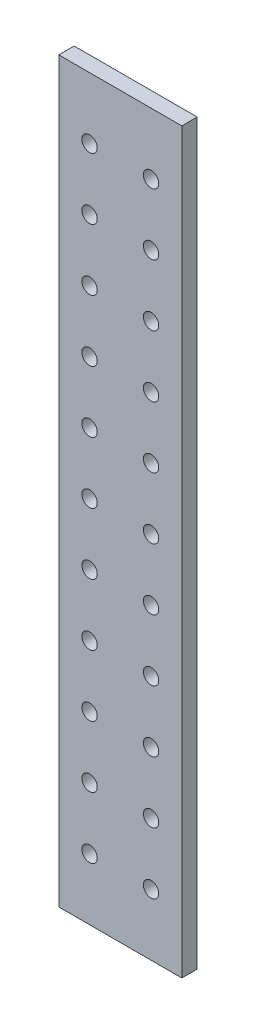
SolidWorks part; units mm, degrees
ref_plane "Front Plane" through (0, 0, 0) normal (0, 0, 1) x (1, 0, 0)
ref_plane "Top Plane" through (0, 0, 0) normal (0, 1, 0) x (1, 0, 0)
ref_plane "Right Plane" through (0, 0, 0) normal (1, 0, 0) x (0, 0, -1)
sketch "Sketch1" plane through (0, 0, 0) normal (0, 0, 1) x (1, 0, 0)
  line L1 (-25.4, 152.4) -> (25.4, 152.4)
  line L2 (-25.4, 152.4) -> (-25.4, -152.4)
  line L3 (-25.4, -152.4) -> (25.4, -152.4)
  line L4 (25.4, 152.4) -> (25.4, -152.4)
  line L5 (-25.4, 152.4) -> (25.4, -152.4) construction
  line L6 (-25.4, -152.4) -> (25.4, 152.4) construction
  point P0 (0, 0)
  dimension "D1" = 50.8
  dimension "D2" = 304.8
extrude "Boss-Extrude1" add sketch "Sketch1" along normal mid plane 6.35
sketch "Sketch2" plane through (0, 0, 0) normal (0, 0, 1) x (1, 0, 0)
  line L0 (25.4, 152.4) -> (-25.4, 152.4) construction
  line L1 (-25.4, 152.4) -> (-25.4, -152.4) construction
  circle A0 centre (-12.7, 127) radius 3.175
  circle A1 centre (12.7, 127) radius 3.175
  circle A2 centre (12.7, 101.6) radius 3.175
  circle A3 centre (12.7, 76.2) radius 3.175
  circle A4 centre (12.7, 50.8) radius 3.175
  circle A5 centre (12.7, 25.4) radius 3.175
  circle A6 centre (12.7, 0) radius 3.175
  circle A7 centre (12.7, -25.4) radius 3.175
  circle A8 centre (12.7, -50.8) radius 3.175
  circle A9 centre (12.7, -76.2) radius 3.175
  circle A10 centre (12.7, -101.6) radius 3.175
  circle A11 centre (-12.7, 101.6) radius 3.175
  circle A12 centre (-12.7, 76.2) radius 3.175
  circle A13 centre (-12.7, 50.8) radius 3.175
  circle A14 centre (-12.7, 25.4) radius 3.175
  circle A15 centre (-12.7, 0) radius 3.175
  circle A16 centre (-12.7, -25.4) radius 3.175
  circle A17 centre (-12.7, -50.8) radius 3.175
  circle A18 centre (-12.7, -76.2) radius 3.175
  circle A19 centre (-12.7, -101.6) radius 3.175
  circle A20 centre (-12.7, -127) radius 3.175
  circle A21 centre (12.7, -127) radius 3.175
  dimension "D1" = 6.35
  dimension "D2" = 25.4
  dimension "D3" = 12.7
  dimension "D4" = 2
  dimension "D5" = 11
extrude "Cut-Extrude1" cut sketch "Sketch2" against normal through all both and the other way through all
